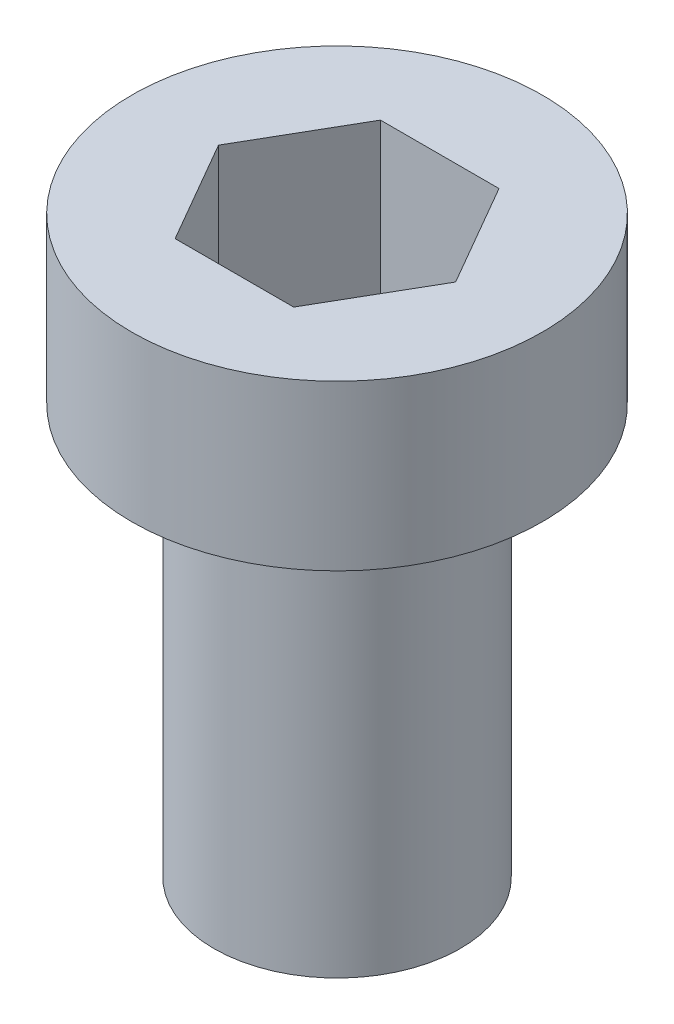
SolidWorks part; units mm, degrees
ref_plane "Front" through (0, 0, 0) normal (0, 0, 1) x (1, 0, 0)
ref_plane "Top" through (0, 0, 0) normal (0, 1, 0) x (1, 0, 0)
ref_plane "Right" through (0, 0, 0) normal (1, 0, 0) x (0, 0, -1)
sketch "Sketch1" plane through (0, 0, 0) normal (0, 1, 0) x (1, 0, 0)
  circle A0 centre (0, 0) radius 3
  dimension "Diameter" = 6
extrude "Extrude1" add sketch "Sketch1" against normal blind 10
sketch "Sketch2" plane through (0, 0, 0) normal (0, 1, 0) x (1, 0, 0)
  line L0 (0, 0) -> (2.8868, 0) construction
  line L1 (2.8868, 0) -> (1.4434, 2.5)
  line L2 (1.4434, 2.5) -> (0, 0) construction
  line L3 (1.4434, -2.5) -> (2.8868, 0)
  line L4 (-1.4434, -2.5) -> (1.4434, -2.5)
  line L5 (-2.8868, 0) -> (-1.4434, -2.5)
  line L6 (-1.4434, 2.5) -> (-2.8868, 0)
  line L7 (1.4434, 2.5) -> (-1.4434, 2.5)
  circle A0 centre (0, 0) radius 5
  dimension "D3" = 10
  dimension "D1" = 60
  dimension "D2" = 2.5
extrude "Extrude2" add sketch "Sketch2" along normal blind 4
